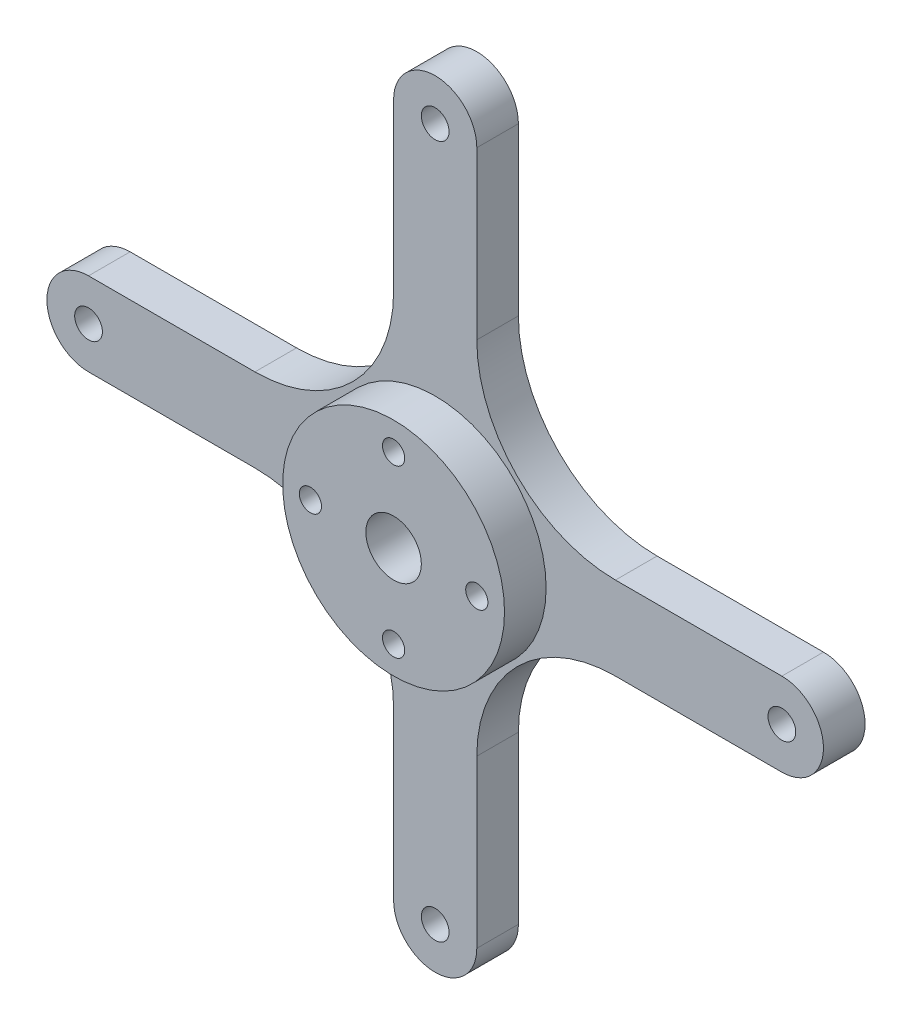
SolidWorks part; units mm, degrees
ref_plane "Front Plane" through (0, 0, 0) normal (0, 0, 1) x (1, 0, 0)
ref_plane "Top Plane" through (0, 0, 0) normal (0, 1, 0) x (1, 0, 0)
ref_plane "Right Plane" through (0, 0, 0) normal (1, 0, 0) x (0, 0, -1)
sketch "Sketch1" plane through (0, 0, 0) normal (0, 0, 1) x (1, 0, 0)
  line L0 (6, 0) -> (-6, 0)
  line L1 (25, 0) -> (-25, 0) construction
  line L2 (25, -3) -> (-25, -3)
  line L3 (25, 3) -> (-25, 3)
  line L4 (0, -25) -> (0, 25) construction
  line L5 (-3, -25) -> (-3, 25)
  line L6 (3, -25) -> (3, 25)
  line L7 (0, 6) -> (0, -6)
  circle A0 centre (-6, 0) radius 0.8
  circle A1 centre (6, 0) radius 0.8
  arc A2 (25, -3) -> (25, 3) centre (25, 0) ccw
  arc A3 (-25, 3) -> (-25, -3) centre (-25, 0) ccw
  arc A4 (-3, -25) -> (3, -25) centre (0, -25) ccw
  arc A5 (3, 25) -> (-3, 25) centre (0, 25) ccw
  circle A6 centre (0, 6) radius 0.8
  circle A7 centre (0, -6) radius 0.8
  point P4 (0, 0)
  point P9 (0, 0)
  point P15 (0, 0)
  point P25 (0, 0)
  dimension "D1" = 1.6
  dimension "D3" = 1.6
  dimension "D5" = 3
  dimension "D7" = 3
  dimension "D8" = 1.6
  dimension "D9" = 1.6
  dimension "D2" = 12
  dimension "D4" = 50
  dimension "D6" = 50
  dimension "D10" = 12
extrude "Boss-Extrude1" add sketch "Sketch1" along normal blind 3
fillet "Fillet1" radius 10 4 edges at (-3, 3, 1.5) (-3, -3, 1.5) (3, -3, 1.5) (3, 3, 1.5)
sketch "Sketch2" plane through (0, 0, 3) normal (0, 0, 1) x (1, 0, 0)
  circle A0 centre (0, 0) radius 2
  dimension "D1" = 4
extrude "Cut-Extrude1" cut sketch "Sketch2" against normal blind 3
sketch "Sketch3" plane through (0, 0, 3) normal (0, 0, 1) x (1, 0, 0)
  circle A0 centre (0, 0) radius 8
  circle A1 centre (0, 0) radius 2
  circle A2 centre (0, 6) radius 0.8
  circle A3 centre (6, 0) radius 0.8
  circle A4 centre (0, -6) radius 0.8
  circle A5 centre (-6, 0) radius 0.8
  dimension "D1" = 16
  dimension "D2" = 1.6
  dimension "D3" = 4
  dimension "D4" = 1.6
  dimension "D5" = 1.6
  dimension "D6" = 1.6
extrude "Boss-Extrude2" add sketch "Sketch3" along normal blind 3
sketch "Sketch4" plane through (0, 0, 3) normal (0, 0, 1) x (1, 0, 0)
  circle A0 centre (0, 25) radius 1
  circle A1 centre (25, 0) radius 1
  circle A2 centre (0, -25) radius 1
  circle A3 centre (-25, 0) radius 1
  point P3 (12.3993, -27.7521)
  point P12 (0, 0)
  dimension "D1" = 2
  dimension "D2" = 4
extrude "Cut-Extrude2" cut sketch "Sketch4" against normal up to vertex (3 mm away) up to point (0, 0, 0)
